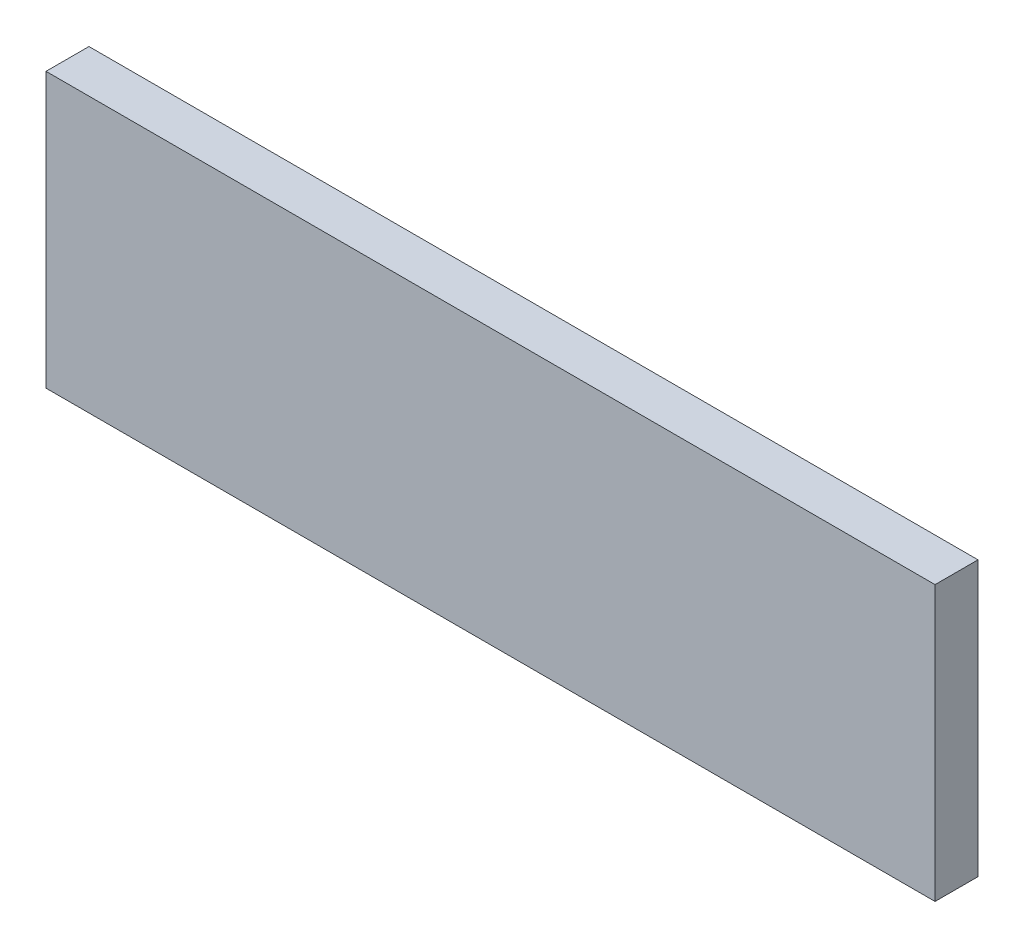
SolidWorks part; units mm, degrees
material "Roble"
ref_plane "Alzado" through (0, 0, 0) normal (0, 0, 1) x (1, 0, 0)
ref_plane "Planta" through (0, 0, 0) normal (0, 1, 0) x (1, 0, 0)
ref_plane "Vista lateral" through (0, 0, 0) normal (1, 0, 0) x (0, 0, -1)
sketch "Croquis1" plane through (0, 0, 0) normal (0, 0, 1) x (1, 0, 0)
  line L1 (-85, -57.5) -> (287.58, -57.5)
  line L2 (-85, -57.5) -> (-85, 57.5)
  line L3 (-85, 57.5) -> (287.58, 57.5)
  line L4 (287.58, -57.5) -> (287.58, 57.5)
  line L5 (-85, -57.5) -> (287.58, 57.5) construction
  line L6 (-85, 57.5) -> (287.58, -57.5) construction
  point P0 (101.29, 0)
  dimension "D1" = 115
  dimension "D2" = 372.58
extrude "Saliente-Extruir1" add sketch "Croquis1" along normal blind 18
